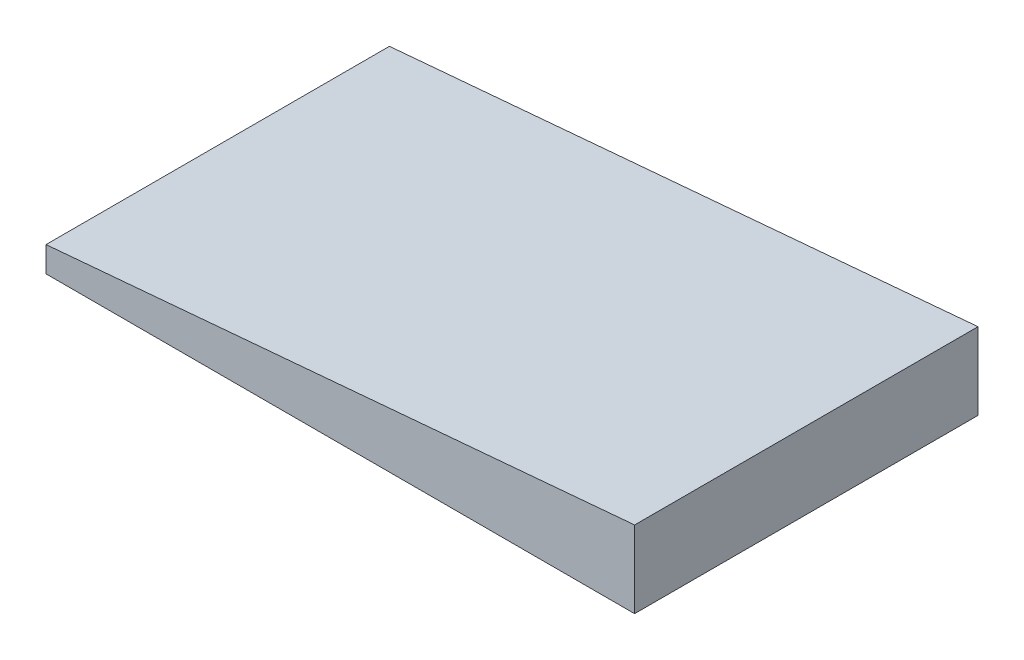
SolidWorks part; units mm, degrees
material "Cedro"
ref_plane "Alzado" through (0, 0, 0) normal (0, 0, 1) x (1, 0, 0)
ref_plane "Planta" through (0, 0, 0) normal (0, 1, 0) x (1, 0, 0)
ref_plane "Vista lateral" through (0, 0, 0) normal (1, 0, 0) x (0, 0, -1)
sketch "Croquis1" plane through (0, 0, 0) normal (0, 0, 1) x (1, 0, 0)
  line L0 (0, 0) -> (0, 50)
  line L1 (0, 50) -> (1160.4, 151.5218)
  line L2 (1160.4, 151.5218) -> (1160.4, 0)
  line L3 (1160.4, 0) -> (0, 0)
  dimension "D1" = 1160.4
  dimension "D2" = 50
  dimension "D3" = 5
extrude "Saliente-Extruir1" add sketch "Croquis1" along normal mid plane 677
shell "Vaciado1" thickness 20
sketch "Croquis2" plane through (0, 0, 0) normal (0, 0, 1) x (1, 0, 0)
  line L0 (20, 31.6734) -> (20, 0)
  line L1 (20, 0) -> (1140.4, 0)
  line L2 (1140.4, 0) -> (1140.4, 129.6957)
  line L3 (1140.4, 129.6957) -> (20, 31.6734)
extrude "Saliente-Extruir2" add sketch "Croquis2" along normal mid plane 20
pattern_linear "MatrizL1" count 2 spacing 170 along (0, 0, 1) of "Saliente-Extruir2"
pattern_linear "MatrizL2" count 2 spacing 170 along (0, 0, -1) of "Saliente-Extruir2"
